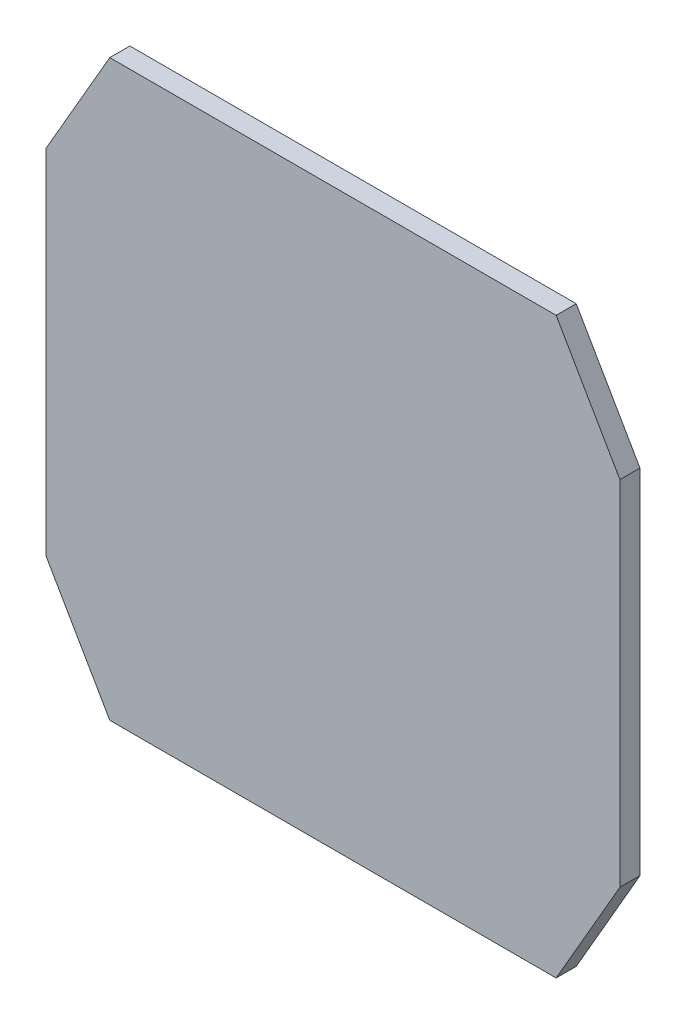
SolidWorks part; units mm, degrees
ref_plane "Piano frontale" through (0, 0, 0) normal (0, 0, 1) x (1, 0, 0)
ref_plane "Piano superiore" through (0, 0, 0) normal (0, 1, 0) x (1, 0, 0)
ref_plane "Piano destro" through (0, 0, 0) normal (1, 0, 0) x (0, 0, -1)
sketch "Schizzo1" plane through (0, 0, 0) normal (0, 0, 1) x (1, 0, 0)
  line L1 (-450, -450) -> (450, -450)
  line L2 (-450, -450) -> (-450, 450)
  line L3 (-450, 450) -> (450, 450)
  line L4 (450, -450) -> (450, 450)
  line L5 (-450, -450) -> (450, 450) construction
  line L6 (-450, 450) -> (450, -450) construction
  point P0 (0, 0)
  dimension "D1" = 900
  dimension "D2" = 900
extrude "Estrusione-Estrusione1" add sketch "Schizzo1" along normal blind 31.5
chamfer "Smusso1" distance 100 angle 60 2 edges at (450, -450, 15.75) (-450, 450, 15.75)
chamfer "Smusso2" distance 100 angle 60 2 edges at (-450, -450, 15.75) (450, 450, 15.75)
